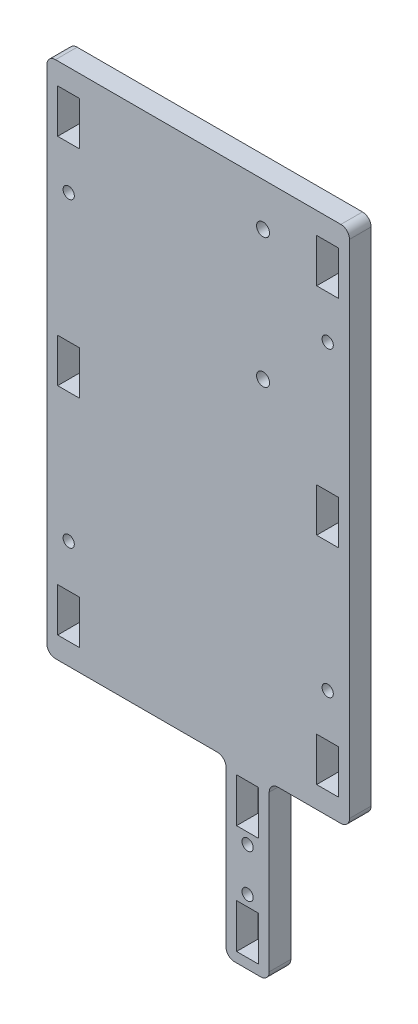
SolidWorks part; units mm, degrees
ref_plane "Front Plane" through (0, 0, 0) normal (0, 0, 1) x (1, 0, 0)
ref_plane "Top Plane" through (0, 0, 0) normal (0, 1, 0) x (1, 0, 0)
ref_plane "Right Plane" through (0, 0, 0) normal (1, 0, 0) x (0, 0, -1)
sketch "Sketch1" plane through (0, 0, 0) normal (0, 0, 1) x (1, 0, 0)
  line L0 (58.9635, -50.8) -> (58.9635, 0) construction
  line L1 (0, 0) -> (88.9, 0)
  line L2 (0, 0) -> (0, 152.4)
  line L3 (0, 152.4) -> (88.9, 152.4)
  line L4 (88.9, 0) -> (88.9, 152.4)
  line L5 (52.6135, 0) -> (65.3135, 0)
  line L6 (52.6135, 0) -> (52.6135, -50.8)
  line L7 (52.6135, -50.8) -> (65.3135, -50.8)
  line L8 (65.3135, 0) -> (65.3135, -50.8)
  line L9 (52.6135, -25.4) -> (65.3135, -25.4) construction
  line L10 (55.725, -34.925) -> (62.202, -34.925)
  line L11 (55.725, -34.925) -> (55.725, -47.879)
  line L12 (55.725, -47.879) -> (62.202, -47.879)
  line L13 (62.202, -34.925) -> (62.202, -47.879)
  line L14 (55.725, -34.925) -> (62.202, -47.879) construction
  line L15 (55.725, -47.879) -> (62.202, -34.925) construction
  line L16 (55.725, -2.921) -> (62.202, -15.875) construction
  line L17 (55.725, -15.875) -> (62.202, -2.921) construction
  line L18 (62.202, -15.875) -> (62.202, -2.921)
  line L19 (55.725, -2.921) -> (62.202, -2.921)
  line L20 (55.725, -15.875) -> (55.725, -2.921)
  line L21 (55.725, -15.875) -> (62.202, -15.875)
  point P11 (58.9635, -41.402)
  point P22 (58.9635, -9.398)
  dimension "D1" = 88.9
  dimension "D2" = 152.4
  dimension "D3" = 50.8
  dimension "D4" = 12.7
  dimension "D5" = 6.477
  dimension "D6" = 19.05
  dimension "D7" = 12.954
  dimension "D8" = 33.175
extrude "Boss-Extrude1" add sketch "Sketch1" along normal blind 6.35 contours L1 L4 L3 L2 | L8 L1 L6 L7 L21 L20 L19 L18 L10 L13 L12 L11
sketch "Sketch3" plane through (0, 0, 6.35) normal (0, 0, 1) x (1, 0, 0)
  line L0 (44.45, 152.4) -> (44.45, 0) construction
  line L1 (0, 76.2) -> (88.9, 76.2) construction
  line L2 (6.4135, 19.177) -> (6.4135, 133.223) construction
  line L3 (3.175, 146.05) -> (9.652, 146.05)
  line L4 (3.175, 146.05) -> (3.175, 133.223)
  line L5 (3.175, 133.223) -> (9.652, 133.223)
  line L6 (9.652, 146.05) -> (9.652, 133.223)
  line L7 (3.175, 19.177) -> (9.652, 19.177)
  line L8 (0, 0) -> (52.6135, 0)
  line L9 (52.6135, 0) -> (52.6135, -50.8)
  line L10 (52.6135, -50.8) -> (65.3135, -50.8)
  line L11 (65.3135, -50.8) -> (65.3135, 0)
  line L12 (65.3135, 0) -> (88.9, 0)
  line L13 (88.9, 0) -> (88.9, 152.4)
  line L14 (88.9, 152.4) -> (0, 152.4)
  line L15 (0, 152.4) -> (0, 0)
  line L16 (0, 0) -> (52.6135, 0)
  line L17 (52.6135, 0) -> (52.6135, -50.8)
  line L18 (52.6135, -50.8) -> (65.3135, -50.8)
  line L19 (65.3135, -50.8) -> (65.3135, 0)
  line L20 (65.3135, 0) -> (88.9, 0)
  line L21 (88.9, 0) -> (88.9, 152.4)
  line L22 (88.9, 152.4) -> (0, 152.4)
  line L23 (0, 152.4) -> (0, 0)
  line L24 (3.175, 19.177) -> (3.175, 6.35)
  line L25 (3.175, 6.35) -> (9.652, 6.35)
  line L26 (9.652, 19.177) -> (9.652, 6.35)
  line L27 (3.175, 82.6135) -> (9.652, 82.6135)
  line L28 (3.175, 82.6135) -> (3.175, 69.7865)
  line L29 (3.175, 69.7865) -> (9.652, 69.7865)
  line L30 (9.652, 82.6135) -> (9.652, 69.7865)
  line L31 (3.175, 82.6135) -> (9.652, 69.7865) construction
  line L32 (3.175, 69.7865) -> (9.652, 82.6135) construction
  line L33 (85.725, 69.7865) -> (79.248, 82.6135) construction
  line L34 (85.725, 82.6135) -> (79.248, 69.7865) construction
  line L35 (82.4865, 19.177) -> (82.4865, 133.223) construction
  line L36 (79.248, 82.6135) -> (79.248, 69.7865)
  line L37 (85.725, 69.7865) -> (79.248, 69.7865)
  line L38 (85.725, 82.6135) -> (85.725, 69.7865)
  line L39 (85.725, 82.6135) -> (79.248, 82.6135)
  line L40 (79.248, 19.177) -> (79.248, 6.35)
  line L41 (85.725, 6.35) -> (79.248, 6.35)
  line L42 (85.725, 19.177) -> (85.725, 6.35)
  line L43 (85.725, 19.177) -> (79.248, 19.177)
  line L44 (79.248, 146.05) -> (79.248, 133.223)
  line L45 (85.725, 133.223) -> (79.248, 133.223)
  line L46 (85.725, 146.05) -> (85.725, 133.223)
  line L47 (85.725, 146.05) -> (79.248, 146.05)
  circle A0 centre (6.4135, 120.523) radius 1.651
  circle A1 centre (6.4135, 31.877) radius 1.651
  circle A2 centre (82.4865, 31.877) radius 1.651
  circle A3 centre (82.4865, 120.523) radius 1.651
  point P20 (6.4135, 76.2)
  point P49 (82.4865, 76.2)
  dimension "D7" = 3.302
  dimension "D2" = 12.827
  dimension "D3" = 6.477
  dimension "D4" = 6.35
  dimension "D5" = 6.35
  dimension "D6" = 3.175
  dimension "D8" = 12.7
  dimension "D1" = 0
extrude "Cut-Extrude3" cut sketch "Sketch3" against normal blind 6.35 contours L6 L3 L4 L5 | L26 L7 L24 L25 | L46 L47 L44 L45 | A0 | L27 L30 L29 L28 | A1 | L40 L41 L42 L43 | A2 | A3 | L36 L37 L38 L39
sketch "Sketch4" plane through (0, 0, 6.35) normal (0, 0, 1) x (1, 0, 0)
  line L0 (58.9635, -15.875) -> (58.9635, -34.925) construction
  line L1 (55.725, -15.875) -> (62.202, -15.875) construction
  line L2 (55.725, -34.925) -> (62.202, -34.925) construction
  line L3 (52.6135, -25.4) -> (65.3135, -25.4) construction
  line L4 (52.6135, 0) -> (52.6135, -50.8) construction
  line L5 (65.3135, 0) -> (65.3135, -50.8) construction
  circle A0 centre (58.9635, -19.05) radius 1.651
  circle A1 centre (58.9635, -31.75) radius 1.651
  dimension "D1" = 3.302
  dimension "D2" = 12.7
extrude "Cut-Extrude4" cut sketch "Sketch4" against normal blind 6.35
fillet "Fillet1" radius 2.54 8 edges at (88.9, 152.4, 3.175) (88.9, 0, 3.175) (65.3135, 0, 3.175) (65.3135, -50.8, 3.175) (52.6135, -50.8, 3.175) (52.6135, 0, 3.175) (0, 0, 3.175) (0, 152.4, 3.175)
sketch "Sketch5" plane through (0, 0, 6.35) normal (0, 0, 1) x (1, 0, 0)
  line L0 (63.5, 152.4) -> (63.5, 0) construction
  line L1 (2.54, 152.4) -> (86.36, 152.4) construction
  line L2 (67.8535, 0) -> (86.36, 0) construction
  line L3 (88.9, 2.54) -> (88.9, 149.86) construction
  circle A0 centre (63.5, 139.7) radius 1.905
  circle A1 centre (63.5, 101.6) radius 1.905
  dimension "D2" = 3.81
  dimension "D1" = 25.4
  dimension "D3" = 38.1
  dimension "D4" = 12.7
extrude "Cut-Extrude5" cut sketch "Sketch5" against normal blind 6.35
